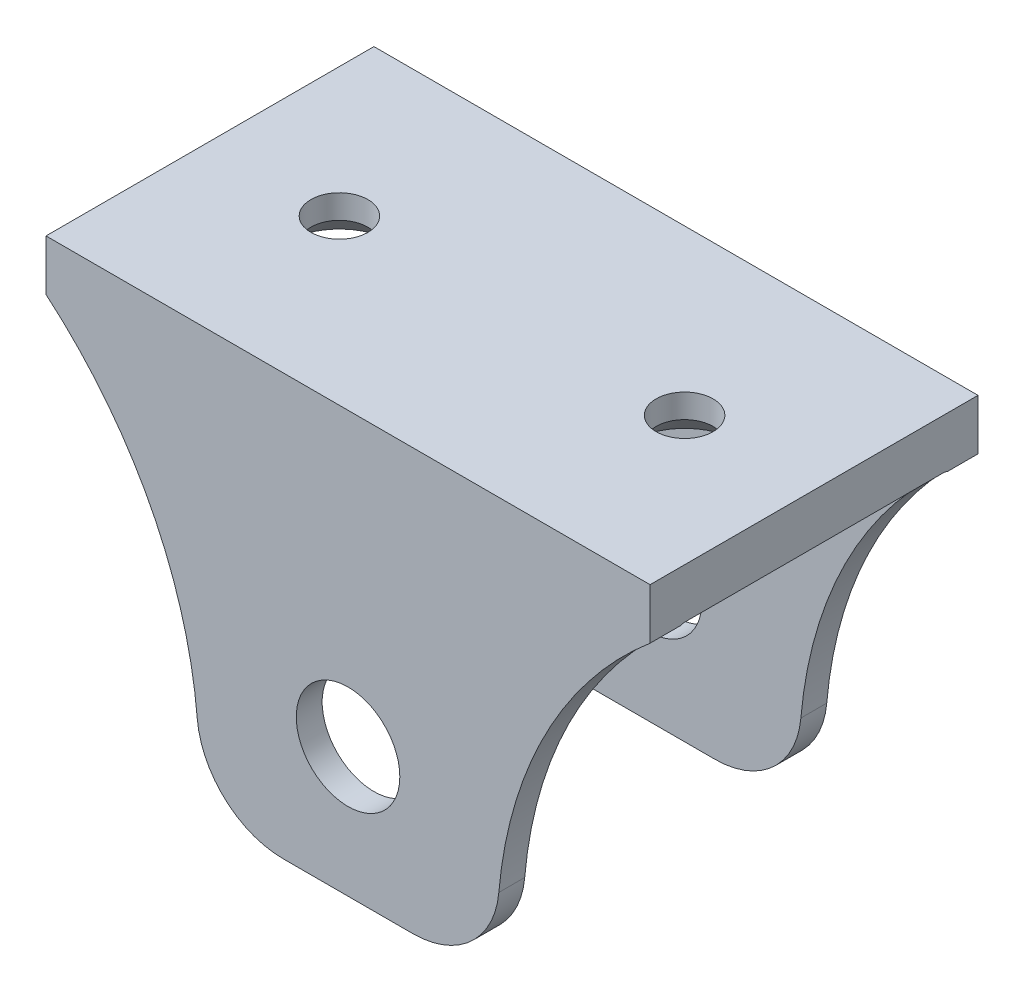
SolidWorks part; units mm, degrees
ref_plane "Płaszczyzna przednia" through (0, 0, 0) normal (0, 0, 1) x (1, 0, 0)
ref_plane "Płaszczyzna górna" through (0, 0, 0) normal (0, 1, 0) x (1, 0, 0)
ref_plane "Płaszczyzna prawa" through (0, 0, 0) normal (1, 0, 0) x (0, 0, -1)
sketch "Szkic1" plane through (0, 0, 0) normal (0, 0, 1) x (1, 0, 0)
  line L0 (0, 48.7686) -> (0, 42.8924)
  line L1 (27.4881, 0) -> (42.5119, 0)
  line L2 (0, 42.8924) -> (0, 48.7686)
  line L3 (0, 48.7686) -> (70, 48.7686)
  line L5 (35, 48.7686) -> (35, -11.9692) construction
  line L6 (70, 42.8924) -> (70, 48.7686)
  line L7 (70, 48.7686) -> (70, 42.8924)
  arc A0 (0, 42.8924) -> (17.5271, 9.1178) centre (-32.278, 4.7069) cw
  arc A1 (42.5119, 0) -> (52.4729, 9.1178) centre (42.5119, 10) ccw
  arc A2 (27.4881, 0) -> (17.5271, 9.1178) centre (27.4881, 10) cw
  arc A3 (70, 42.8924) -> (52.4729, 9.1178) centre (102.278, 4.7069) ccw
  circle A4 centre (35, 15) radius 6
  point P1 (35, 0)
  point P7 (52.5, 0)
  point P10 (35, 0)
  point P13 (35, 48.7686)
  point P15 (17.5, 0)
  point P18 (35, 48.7686)
  dimension "D1" = 50
  dimension "D3" = 10
  dimension "D2" = 15
extrude "Dodanie-wyciągnięcie1" add sketch "Szkic1" along normal blind 38
sketch "Szkic2" plane through (0, 0, 0) normal (0, -1, 0) x (1, 0, 0)
  line L14 (0, 3) -> (70, 3)
  line L16 (0, 35) -> (70, 35)
  line L23 (0, 35) -> (0, 3)
  line L24 (70, 35) -> (70, 3)
extrude "Wytnij-wyciągnięcie1" cut sketch "Szkic2" against normal blind 43
fillet "Zaokrąglenie1" radius 1 2 edges at (35, 43, 35) (35, 43, 3)
hole_wizard "Pogłębienie stożkowe pod M6 Śrubę z łbem soczewkowym1" positions "Szkic 3D1" profile "Szkic5" countersink size "M6" standard "ISO" end condition through all
sketch3d "Szkic 3D1"
  line L0 (0, 43, 34) -> (0, 43, 4) construction
  line L2 (70, 43, 19) -> (2.7425, 43, 19) construction
  point P0 (15, 43, 19)
  point P2 (55, 43, 19)
  dimension "D3" = 0
  dimension "D1" = 40
  dimension "D2" = 15
sketch "Szkic5" plane through (15, 43, 19) normal (1, 0, 0) x (0, 0, -1)
  line L0 (0, 0) -> (0, 5.7686)
  line L1 (0, 5.7686) -> (3.3, 5.7686)
  line L2 (3.3, 5.7686) -> (3.3, 3)
  line L3 (3.3, 3) -> (6.3, 0)
  line L5 (6.3, 0) -> (0, 0)
  line L6 (-3.3, 3) -> (-6.3, 0) construction
  line L11 (0, -6.35) -> (0, 107.95) construction
  dimension "Średnica otworu na wylot" = 6.6
  dimension "Głębokość otworu na wylot" = 5.7686
  dimension "Średnica zewnętrznego pogłębienia stożkowego" = 12.6
  dimension "Kąt zewnętrznego pogłębienia stożkowego" = 90
